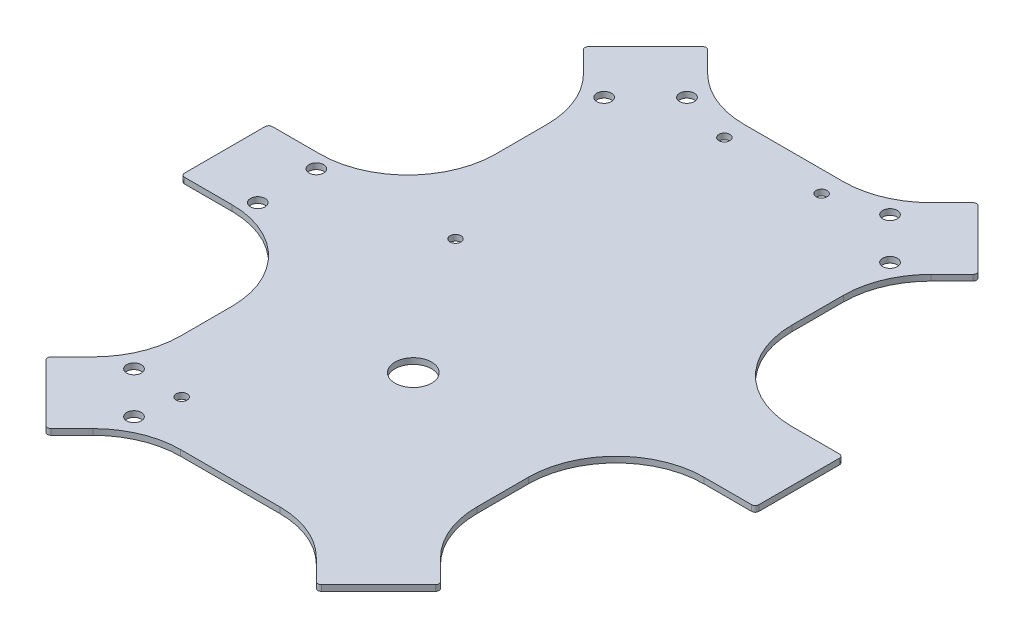
SolidWorks part; units mm, degrees
material "1060 合金"
ref_plane "前视基准面" through (0, 0, 0) normal (0, 0, 1) x (1, 0, 0)
ref_plane "上视基准面" through (0, 0, 0) normal (0, 1, 0) x (1, 0, 0)
ref_plane "右视基准面" through (0, 0, 0) normal (1, 0, 0) x (0, 0, -1)
other "Configuration Table"
sketch "草图1" [suppressed] plane through (0, 0, 0) normal (0, 1, 0) x (1, 0, 0)
  line L30 (25, 78.9) -> (40.5563, 63.3436)
  line L32 (40.5563, -46.6564) -> (25, -62.2127)
  line L33 (30.8579, 84.7578) -> (39.1421, 93.0421)
  line L34 (-16.7157, -62.2127) -> (16.7157, -62.2127)
  line L35 (0, 87.4232) -> (0, -140.4118) construction
  line L36 (40.5563, 93.0421) -> (54.6985, 78.9)
  line L37 (54.6985, 77.4858) -> (46.4142, 69.2015)
  line L38 (60.5563, 19.3436) -> (80.5563, 19.3436)
  line L39 (81.5563, 18.3436) -> (81.5563, -1.6564)
  line L40 (80.5563, -2.6564) -> (60.5563, -2.6564)
  line L41 (-52.5772, -89.7899) -> (-30.8579, -68.0706)
  line L42 (40.5563, 55.0594) -> (40.5563, 39.3436)
  line L43 (46.4142, -52.5142) -> (68.1335, -74.2335)
  line L44 (68.1335, -75.6477) -> (53.9914, -89.7899)
  line L45 (52.5772, -89.7899) -> (30.8579, -68.0706)
  line L46 (16.7157, 78.9) -> (-16.7157, 78.9)
  line L47 (-68.1335, -75.6477) -> (-53.9914, -89.7899)
  line L48 (-46.4142, -52.5142) -> (-68.1335, -74.2335)
  line L49 (-40.5563, 55.0837) -> (-40.5563, 39.3436)
  line L50 (-80.5563, -2.6564) -> (-60.5563, -2.6564)
  line L51 (-81.5563, 18.3436) -> (-81.5563, -1.6564)
  line L57 (-40.5563, 8.3436) -> (40.5563, 8.3436) construction
  line L59 (-60.5563, 19.3436) -> (-80.5563, 19.3436)
  line L67 (-54.6706, 77.5166) -> (-46.3849, 69.1964)
  line L68 (-40.5563, 93.0421) -> (-54.6691, 78.9294)
  line L69 (-30.8579, 84.7578) -> (-39.1421, 93.0421)
  line L70 (-40.5563, -46.6564) -> (-25, -62.2127)
  line L71 (-25, 78.9) -> (-40.5563, 63.3436)
  line L72 (40.5563, -22.6564) -> (40.5563, -38.3721)
  line L73 (-40.5563, -22.6564) -> (-40.5563, -38.3721)
  arc A0 (-16.7157, -62.2127) -> (-30.8579, -68.0706) centre (-16.7157, -82.2127) ccw
  arc A1 (-40.5563, -38.3721) -> (-46.4142, -52.5142) centre (-60.5563, -38.3721) cw
  arc A2 (-40.5563, -22.6564) -> (-60.5563, -2.6564) centre (-60.5563, -22.6564) ccw
  arc A3 (-40.5563, 39.3436) -> (-60.5563, 19.3436) centre (-60.5563, 39.3436) cw
  arc A4 (-46.3849, 69.1964) -> (-40.5563, 55.0837) centre (-60.5563, 55.0837) cw
  arc A5 (-30.8579, 84.7578) -> (-16.7157, 78.9) centre (-16.7157, 98.9) ccw
  arc A6 (16.7157, -62.2127) -> (30.8579, -68.0706) centre (16.7157, -82.2127) cw
  arc A7 (40.5563, -38.3721) -> (46.4142, -52.5142) centre (60.5563, -38.3721) ccw
  arc A8 (40.5563, -22.6564) -> (60.5563, -2.6564) centre (60.5563, -22.6564) cw
  arc A9 (40.5563, 39.3436) -> (60.5563, 19.3436) centre (60.5563, 39.3436) ccw
  arc A10 (40.5563, 55.0594) -> (46.4142, 69.2015) centre (60.5563, 55.0594) cw
  arc A11 (30.8579, 84.7578) -> (16.7157, 78.9) centre (16.7157, 98.9) cw
  arc A12 (-81.5563, 18.3436) -> (-80.5563, 19.3436) centre (-80.5563, 18.3436) cw
  arc A13 (-80.5563, -2.6564) -> (-81.5563, -1.6564) centre (-80.5563, -1.6564) cw
  arc A14 (-68.1335, -75.6477) -> (-68.1335, -74.2335) centre (-67.4264, -74.9406) cw
  arc A15 (-52.5772, -89.7899) -> (-53.9914, -89.7899) centre (-53.2843, -89.0828) cw
  arc A16 (68.1335, -74.2335) -> (68.1335, -75.6477) centre (67.4264, -74.9406) cw
  arc A17 (53.9914, -89.7899) -> (52.5772, -89.7899) centre (53.2843, -89.0828) cw
  arc A18 (81.5563, -1.6564) -> (80.5563, -2.6564) centre (80.5563, -1.6564) cw
  arc A19 (80.5563, 19.3436) -> (81.5563, 18.3436) centre (80.5563, 18.3436) cw
  arc A20 (54.6985, 78.9) -> (54.6985, 77.4858) centre (53.9914, 78.1929) cw
  arc A21 (39.1421, 93.0421) -> (40.5563, 93.0421) centre (39.8492, 92.335) cw
  arc A22 (-39.1421, 93.0421) -> (-40.5563, 93.0421) centre (-39.8492, 92.335) ccw
  arc A23 (-54.6706, 77.5166) -> (-54.6691, 78.9294) centre (-53.962, 78.2223) cw
  point P18 (-40.5563, -2.6564)
  point P29 (-40.5563, 19.3436)
  point P31 (0, 78.9)
  point P55 (40.5563, -2.6564)
  point P58 (40.5563, 19.3436)
  point P67 (-81.5563, 19.3436)
  point P70 (-81.5563, -2.6564)
  point P73 (-68.8406, -74.9406)
  point P76 (-53.2843, -90.497)
  point P79 (68.8406, -74.9406)
  point P82 (53.2843, -90.497)
  point P85 (81.5563, -2.6564)
  point P88 (81.5563, 19.3436)
  dimension "D1" = 20
  dimension "D2" = 1
  dimension "D3" = 19
  dimension "D4" = 19
  dimension "D5" = 22
  dimension "D6" = 41
sketch "草图5" plane through (0, 0, 0) normal (0, 1, 0) x (1, 0, 0)
  line L0 (0.6655, 1.7957) -> (0.1696, 1.7957)
  line L1 (0.1696, 1.7955) -> (0.1696, 5.326) construction
  line L2 (0.8947, 2.0889) -> (0.1696, 2.0889)
  line L3 (0.8947, 2.0889) -> (2.0148, 1.2751)
  line L4 (2.0148, 1.2751) -> (2.0148, 1.0558)
  line L5 (2.0148, 1.0558) -> (1.2081, -0.6653)
  line L6 (1.2081, -0.6653) -> (1.8365, -2.2852)
  line L7 (1.8365, -2.2852) -> (0.7016, -3.1098)
  line L8 (0.7016, -3.1098) -> (0.1696, -3.1098)
  line L9 (2.4149, -2.4153) -> (0.9633, -3.47)
  line L10 (0.9633, -3.47) -> (0.7016, -3.1098)
  line L11 (2.4149, -2.4153) -> (1.497, -0.049)
  line L12 (1.7081, -0.5932) -> (1.2492, -0.7713)
  line L13 (2.2113, -1.8902) -> (1.7523, -2.0683)
  line L14 (0.9633, -3.47) -> (0.1696, -3.47)
  line L15 (2.0982, -2.6454) -> (1.8365, -2.2852)
  line L16 (1.7081, -1.9542) -> (1.7081, -2.3786)
  line L17 (0.9633, -3.47) -> (0.9633, -5.3331)
  line L18 (0.9633, -5.3331) -> (-0.6241, -5.3331)
  line L19 (0.9633, -4.5041) -> (0.1696, -4.5041)
  line L20 (1.4029, 4.1544) -> (0.1696, 4.1544) construction
  line L21 (3.0798, -0.1534) -> (3.0798, -3.4472) construction
  line L22 (-2.7406, -0.1534) -> (-2.7406, -3.4472) construction
  line L23 (-0.6241, -3.47) -> (-0.6241, -5.3331)
  line L24 (-0.6241, -3.47) -> (0.1696, -3.47)
  line L25 (-0.3624, -3.1098) -> (0.1696, -3.1098)
  line L26 (-1.4973, -2.2852) -> (-0.3624, -3.1098)
  line L27 (-1.3689, -1.9542) -> (-1.3689, -2.3786)
  line L28 (-0.8689, -0.6653) -> (-1.4973, -2.2852)
  line L29 (-1.3689, -0.5932) -> (-0.91, -0.7713)
  line L30 (-1.0637, 4.1544) -> (0.1696, 4.1544) construction
  line L31 (-1.6756, 1.0558) -> (-0.8689, -0.6653)
  line L32 (-1.6756, 1.2751) -> (-1.6756, 1.0558)
  line L33 (-0.5555, 2.0889) -> (-1.6756, 1.2751)
  line L34 (-0.5555, 2.0889) -> (0.1696, 2.0889)
  line L35 (-0.3263, 1.7957) -> (0.1696, 1.7957)
  line L36 (-1.759, -2.6454) -> (-1.4973, -2.2852)
  line L37 (-1.872, -1.8902) -> (-1.4131, -2.0683)
  line L38 (-2.0757, -2.4153) -> (-1.1578, -0.049)
  line L39 (-2.0757, -2.4153) -> (-0.6241, -3.47)
  line L40 (-0.6241, -4.5041) -> (0.1696, -4.5041)
  point P56 (0.1696, -5.3331)
  dimension "D1" = 144
  dimension "D2" = 144
sketch "草图6" [suppressed] plane through (0, 0, 0) normal (0, 1, 0) x (1, 0, 0)
  line L0 (-2.75, 0) -> (2.75, 0) construction
  line L1 (-54.2835, 48) -> (-88.2861, 82.0025)
  line L2 (-88.2861, 82.0025) -> (-58.5876, 111.701)
  line L3 (-58.5876, 111.701) -> (-32.4014, 85.5148)
  line L4 (-60.4337, 21) -> (-101.8, 21)
  line L5 (-101.8, 21) -> (-101.8, -21)
  line L6 (-101.8, -21) -> (-60.4337, -21)
  line L7 (-54.2835, -48) -> (-88.2861, -82.0025)
  line L8 (-58.5876, -111.701) -> (-32.4014, -85.5148)
  line L9 (-88.2861, -82.0025) -> (-58.5876, -111.701)
  line L10 (-73.4369, 96.8518) -> (-45.1526, 68.5675)
  line L11 (-101.8, 0) -> (-61.8, 0)
  line L12 (-73.4369, -96.8518) -> (-45.1526, -68.5675)
  line L13 (0, -137.0204) -> (0, 137.0204) construction
  ellipse E0 centre (0, 0) end of major axis (0, 100.4241) minor radius 61.8
  dimension "D1" = 48
  dimension "D2" = 24
  dimension "D3" = 45
  dimension "D4" = 24
  dimension "D5" = 12
  dimension "D6" = 19
  dimension "D7" = 40
  dimension "D8" = 73.4369
  dimension "D9" = 96.8518
sketch "草图7" [suppressed] plane through (0, 0, 0) normal (0, 0, 1) x (1, 0, 0)
  line L0 (32.3745, -44.4151) -> (32.3981, -38.3402)
  line L2 (10.7336, -68.0209) -> (32.3745, -44.4151)
  line L3 (0, -68.0206) -> (10.7336, -68.0209)
  line L8 (32.3981, -38.3402) -> (17.3573, 0)
  line L10 (-17.3573, 0) -> (17.3573, 0)
  line L20 (35.7261, 42.3907) -> (35.6862, 45.8735)
  line L21 (17.3918, 3.5) -> (35.7261, 42.3907)
  line L22 (-17.3918, 3.5) -> (17.3918, 3.5)
  line L28 (12.7226, 62.5615) -> (-12.7226, 62.5615)
  line L29 (35.6862, 45.8735) -> (12.7226, 62.5615)
  line L30 (25, 80.3142) -> (41.9706, 63.3436)
  line L32 (41.9706, -46.6564) -> (25, -63.6269)
  line L33 (25, 80.3142) -> (53.2843, 108.5985)
  line L34 (-25, -63.6269) -> (25, -63.6269)
  line L35 (0, 87.4232) -> (0, -140.4118) construction
  line L36 (53.2843, 108.5985) -> (70.2548, 91.6279)
  line L37 (70.2548, 91.6279) -> (41.9706, 63.3436)
  line L38 (41.9706, 20.3436) -> (81.9706, 20.3436)
  line L39 (81.9706, 20.3436) -> (81.9706, -3.6564)
  line L40 (81.9706, -3.6564) -> (41.9706, -3.6564)
  line L41 (-53.2843, -91.9112) -> (-25, -63.6269)
  line L42 (41.9706, 63.3436) -> (41.9706, -46.6564)
  line L43 (41.9706, -46.6564) -> (70.2548, -74.9406)
  line L44 (70.2548, -74.9406) -> (53.2843, -91.9112)
  line L45 (53.2843, -91.9112) -> (25, -63.6269)
  line L46 (25, 80.3142) -> (-25, 80.3142)
  line L47 (-70.2548, -74.9406) -> (-53.2843, -91.9112)
  line L48 (-41.9706, -46.6564) -> (-70.2548, -74.9406)
  line L49 (-41.9706, 63.3436) -> (-41.9706, -46.6564)
  line L50 (-81.9706, -3.6564) -> (-41.9706, -3.6564)
  line L51 (-81.9706, 20.3436) -> (-81.9706, -3.6564)
  line L57 (-41.9706, 8.3436) -> (41.9706, 8.3436) construction
  line L59 (-41.9706, 20.3436) -> (-81.9706, 20.3436)
  line L66 (0, -68.0206) -> (-10.7336, -68.0209)
  line L67 (-70.2548, 91.7457) -> (-41.9706, 63.3436)
  line L68 (-53.3432, 108.6574) -> (-70.2548, 91.7457)
  line L69 (-25, 80.3142) -> (-53.3432, 108.6574)
  line L70 (-41.9706, -46.6564) -> (-25, -63.6269)
  line L71 (-25, 80.3142) -> (-41.9706, 63.3436)
  line L72 (-35.6862, 45.8735) -> (-12.7226, 62.5615)
  line L73 (-17.3918, 3.5) -> (-35.7261, 42.3907)
  line L74 (-35.7261, 42.3907) -> (-35.6862, 45.8735)
  line L75 (-32.3981, -38.3402) -> (-17.3573, 0)
  line L76 (-10.7336, -68.0209) -> (-32.3745, -44.4151)
  line L77 (-32.3745, -44.4151) -> (-32.3981, -38.3402)
  point P31 (0, 80.3142)
  point P45 (0, 62.5615)
  point P46 (0, 3.5)
  point P48 (0, 0)
  dimension "D1" = 24
  dimension "D2" = 24
  dimension "D3" = 135
  dimension "D4" = 12
  dimension "D5" = 40
  dimension "D6" = 110
  dimension "D7" = 40
  dimension "D8" = 24
  dimension "D9" = 50
  dimension "D11" = 40
sketch "草图8" plane through (0, 0, 0) normal (0, -1, 0) x (1, 0, 0)
  line L30 (23.5, 76.9706) -> (40.4706, 60)
  line L32 (40.4706, -60) -> (23.5, -76.9706)
  line L33 (30.5294, 84) -> (36.2279, 89.6985)
  line L34 (-13.5589, -76.9706) -> (13.5589, -76.9706)
  line L35 (0, 87.4232) -> (0, -140.4118) construction
  line L36 (37.6421, 89.6985) -> (53.1985, 74.1421)
  line L37 (53.1985, 72.7279) -> (47.5, 67.0294)
  line L38 (64.4706, 12) -> (77.4706, 12)
  line L39 (78.4706, 11) -> (78.4706, -11)
  line L40 (77.4706, -12) -> (64.4706, -12)
  line L41 (-36.2279, -89.6985) -> (-30.5294, -84)
  line L42 (40.4706, 50.0589) -> (40.4706, 36)
  line L43 (47.5, -67.0294) -> (53.1985, -72.7279)
  line L44 (53.1985, -74.1421) -> (37.6421, -89.6985)
  line L45 (36.2279, -89.6985) -> (30.5294, -84)
  line L46 (13.5589, 76.9706) -> (-13.5589, 76.9706)
  line L47 (-53.1985, -74.1421) -> (-37.6421, -89.6985)
  line L48 (-47.5, -67.0294) -> (-53.1985, -72.7279)
  line L49 (-40.4706, 50.0589) -> (-40.4706, 36)
  line L50 (-77.4706, -12) -> (-64.4706, -12)
  line L51 (-78.4706, 11) -> (-78.4706, -11)
  line L57 (-55.7635, 0) -> (25.3492, 0) construction
  line L59 (-64.4706, 12) -> (-77.4706, 12)
  line L67 (-53.1985, 72.7279) -> (-47.5, 67.0294)
  line L68 (-37.6421, 89.6985) -> (-53.1985, 74.1421)
  line L69 (-30.5294, 84) -> (-36.2279, 89.6985)
  line L70 (-40.4706, -60) -> (-23.5, -76.9706)
  line L71 (-23.5, 76.9706) -> (-40.4706, 60)
  line L72 (-40.4706, -36) -> (-40.4706, -50.0589)
  line L73 (40.4706, -36) -> (40.4706, -50.0589)
  arc A0 (-40.4706, -50.0589) -> (-47.5, -67.0294) centre (-64.4706, -50.0589) cw
  arc A1 (-13.5589, -76.9706) -> (-30.5294, -84) centre (-13.5589, -100.9706) ccw
  arc A2 (30.5294, -84) -> (13.5589, -76.9706) centre (13.5589, -100.9706) ccw
  arc A3 (47.5, -67.0294) -> (40.4706, -50.0589) centre (64.4706, -50.0589) cw
  arc A4 (64.4706, -12) -> (40.4706, -36) centre (64.4706, -36) ccw
  arc A5 (-64.4706, -12) -> (-40.4706, -36) centre (-64.4706, -36) cw
  arc A6 (-64.4706, 12) -> (-40.4706, 36) centre (-64.4706, 36) ccw
  arc A7 (40.4706, 36) -> (64.4706, 12) centre (64.4706, 36) ccw
  arc A8 (40.4706, 50.0589) -> (47.5, 67.0294) centre (64.4706, 50.0589) cw
  arc A9 (13.5589, 76.9706) -> (30.5294, 84) centre (13.5589, 100.9706) ccw
  arc A10 (-13.5589, 76.9706) -> (-30.5294, 84) centre (-13.5589, 100.9706) cw
  arc A11 (-40.4706, 50.0589) -> (-47.5, 67.0294) centre (-64.4706, 50.0589) ccw
  arc A12 (-78.4706, 11) -> (-77.4706, 12) centre (-77.4706, 11) cw
  arc A13 (-77.4706, -12) -> (-78.4706, -11) centre (-77.4706, -11) cw
  arc A14 (-53.1985, -74.1421) -> (-53.1985, -72.7279) centre (-52.4914, -73.435) cw
  arc A15 (-36.2279, -89.6985) -> (-37.6421, -89.6985) centre (-36.935, -88.9914) cw
  arc A16 (37.6421, -89.6985) -> (36.2279, -89.6985) centre (36.935, -88.9914) cw
  arc A17 (53.1985, -72.7279) -> (53.1985, -74.1421) centre (52.4914, -73.435) cw
  arc A18 (78.4706, -11) -> (77.4706, -12) centre (77.4706, -11) cw
  arc A19 (77.4706, 12) -> (78.4706, 11) centre (77.4706, 11) cw
  arc A20 (53.1985, 74.1421) -> (53.1985, 72.7279) centre (52.4914, 73.435) cw
  arc A21 (36.2279, 89.6985) -> (37.6421, 89.6985) centre (36.935, 88.9914) cw
  arc A22 (-53.1985, 72.7279) -> (-53.1985, 74.1421) centre (-52.4914, 73.435) cw
  arc A23 (-37.6421, 89.6985) -> (-36.2279, 89.6985) centre (-36.935, 88.9914) cw
  circle A25 centre (-27.7426, 75.5563) radius 1 construction
  circle A26 centre (-39.0563, 64.2426) radius 1 construction
  circle A28 centre (-27.7426, 75.5563) radius 1
  circle A30 centre (-39.0563, 64.2426) radius 1
  circle A32 centre (-39.0563, 64.2426) radius 2
  circle A34 centre (-27.7426, 75.5563) radius 2
  circle A36 centre (0, 26.9706) radius 5
  circle A37 centre (-61.4706, 8) radius 2 construction
  circle A38 centre (-61.4706, -8) radius 2 construction
  circle A39 centre (-25.888, -10.4468) radius 1.5 construction
  circle A40 centre (-25.888, 64.388) radius 1.5 construction
  circle A41 centre (-61.4706, 8) radius 2
  circle A42 centre (-61.4706, -8) radius 2
  circle A43 centre (-25.888, -10.4468) radius 1.5
  circle A44 centre (-25.888, 64.388) radius 1.5
  circle A45 centre (27.7426, -75.5563) radius 2
  circle A46 centre (39.0563, -64.2426) radius 2
  circle A47 centre (-27.7426, -75.5563) radius 2
  circle A48 centre (-39.0563, -64.2426) radius 2
  circle A49 centre (13.4278, -71.1706) radius 1.5 construction
  circle A50 centre (-13.1298, -71.1706) radius 1.5 construction
  circle A51 centre (13.4278, -71.1706) radius 1.5
  circle A52 centre (-13.1298, -71.1706) radius 1.5
  circle A53 centre (-61.4706, 8) radius 2
  circle A54 centre (-61.4706, -8) radius 2
  point P31 (0, 76.9706)
  point P34 (40.4706, -12)
  point P42 (-40.4706, -12)
  point P46 (-40.4706, 12)
  point P50 (40.4706, 12)
  point P68 (-78.4706, 12)
  point P71 (-78.4706, -12)
  point P74 (-53.9056, -73.435)
  point P77 (-36.935, -90.4056)
  point P80 (36.935, -90.4056)
  point P83 (53.9056, -73.435)
  point P86 (78.4706, -12)
  point P89 (78.4706, 12)
  point P92 (53.9056, 73.435)
  point P95 (36.935, 90.4056)
  dimension "D2" = 24
  dimension "D12" = 24
  dimension "D13" = 1
  dimension "D15" = 10
  dimension "D16" = 4
  dimension "D17" = 4
  dimension "D18" = 4
  dimension "D19" = 4
  dimension "D20" = 4
  dimension "D21" = 4
  dimension "D5" = 19
  dimension "D7" = 19
  dimension "D1" = 24
  dimension "D6" = 120
  dimension "D3" = 135
  dimension "D4" = 12
  dimension "D8" = 24
  dimension "D9" = 19
  dimension "D11" = 47
  dimension "D10" = 38
  dimension "D14" = 50
extrude "凸台-拉伸1" add sketch "草图8" along normal blind 1.6
equation "\"l\"=19"
equation "\"w\"=24"
equation "\"D2@草图6\"=\"w\""
equation "\"D4@草图6\"=\"w\""
equation "\"D5@草图6\"=\"w\"/2"
equation "\"D6@草图6\"=\"l\""
equation "\"D3@草图1\"=\"l\""
equation "\"D4@草图1\"=\"l\""
equation "\"D5@草图8\"=\"l\""
equation "\"D9@草图8\"=\"l\""
equation "\"D7@草图8\"=\"l\""
equation "\"D2@草图8\"=\"w\""
equation "\"D8@草图8\"=\"w\""
equation "\"D1@草图8\"=\"w\""
equation "\"D4@草图8\"=\"w\"/2"
equation "\"w_body\"=47"
equation "\"D11@草图8\"=\"w_body\""
equation "\"l_mid\"=38"
equation "\"D10@草图8\"=\"l_mid\""
